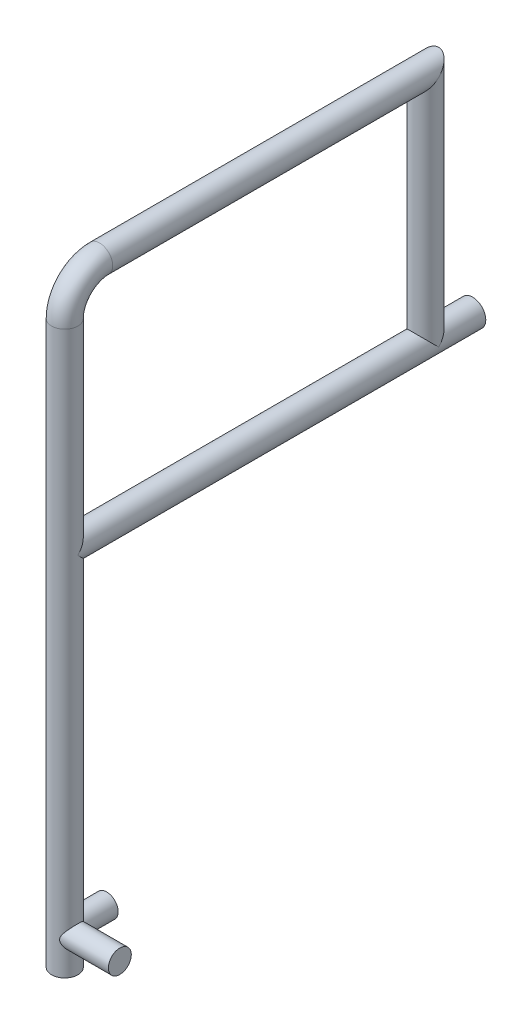
SolidWorks part; units mm, degrees
ref_plane "Front Plane" through (0, 0, 0) normal (0, 0, 1) x (1, 0, 0)
ref_plane "Top Plane" through (0, 0, 0) normal (0, 1, 0) x (1, 0, 0)
ref_plane "Right Plane" through (0, 0, 0) normal (1, 0, 0) x (0, 0, -1)
sketch "Sketch2" plane through (0, 0, 0) normal (0, 1, 0) x (1, 0, 0)
  circle A0 centre (0, 0) radius 20
  dimension "D1" = 40
sketch "Sketch3" plane through (0, 0, 0) normal (1, 0, 0) x (0, 0, -1)
  line L0 (0, 0) -> (0, 302.8198)
  line L1 (53.1445, 355.9643) -> (550.0943, 355.9643)
  line L2 (550.0943, 355.9643) -> (550.0943, 0.0943)
  arc A0 (0, 302.8198) -> (53.1445, 355.9643) centre (53.1445, 302.8198) cw
  point P8 (0, 0)
  dimension "D4" = 53.1445
  dimension "D1" = 550.0943
  dimension "D2" = 355.87
  dimension "D3" = 302.8198
sweep "Sweep1" add profiles "Sketch2" path "Sketch3"
sketch "Sketch5" plane through (0, 0, 0) normal (0, -1, 0) x (1, 0, 0)
  circle A1 centre (0, 0) radius 20
  circle A2 centre (0, 0) radius 20
  dimension "D1" = 0
extrude "Boss-Extrude1" add sketch "Sketch5" along normal blind 553.9061
sketch "Sketch6" plane through (0, 0, 0) normal (0, 0, 1) x (1, 0, 0)
  circle A0 centre (0, 0) radius 20
  dimension "D1" = 40
extrude "Boss-Extrude2" add sketch "Sketch6" against normal blind 622
sketch "Sketch7" plane through (0, 0, -622) normal (0, 0, -1) x (-1, 0, 0)
  line L0 (-20, 0) -> (20, 0) construction
  circle A0 centre (0, 0) radius 17.5
  dimension "D1" = 35
extrude "Cut-Extrude1" cut sketch "Sketch7" against normal blind 286
sketch "Sketch8" plane through (0, 0, 0) normal (0, 0, 1) x (1, 0, 0)
  line L0 (-20, -553.9061) -> (20, -553.9061) construction
  line L2 (0, -553.9061) -> (0, -477.4463) construction
  circle A0 centre (0, -503.9061) radius 17.5
  point P4 (-2.2802, -503.9061)
  point P5 (0, 0)
  dimension "D1" = 35
  dimension "D2" = 50
extrude "Boss-Extrude4" add sketch "Sketch8" against normal blind 64
sketch "Sketch11" plane through (0, 0, 0) normal (1, 0, 0) x (0, 0, -1)
  line L0 (64, -503.9061) -> (-49.7267, -503.9061) construction
  line L1 (64, -521.4061) -> (64, -486.4061) construction
  line L2 (0, -553.9061) -> (0, -466.0136) construction
  line L3 (-20, -553.9061) -> (20, -553.9061) construction
  circle A0 centre (0, -503.9061) radius 17.5
  dimension "D1" = 35
extrude "Boss-Extrude5" add sketch "Sketch11" along normal blind 84
